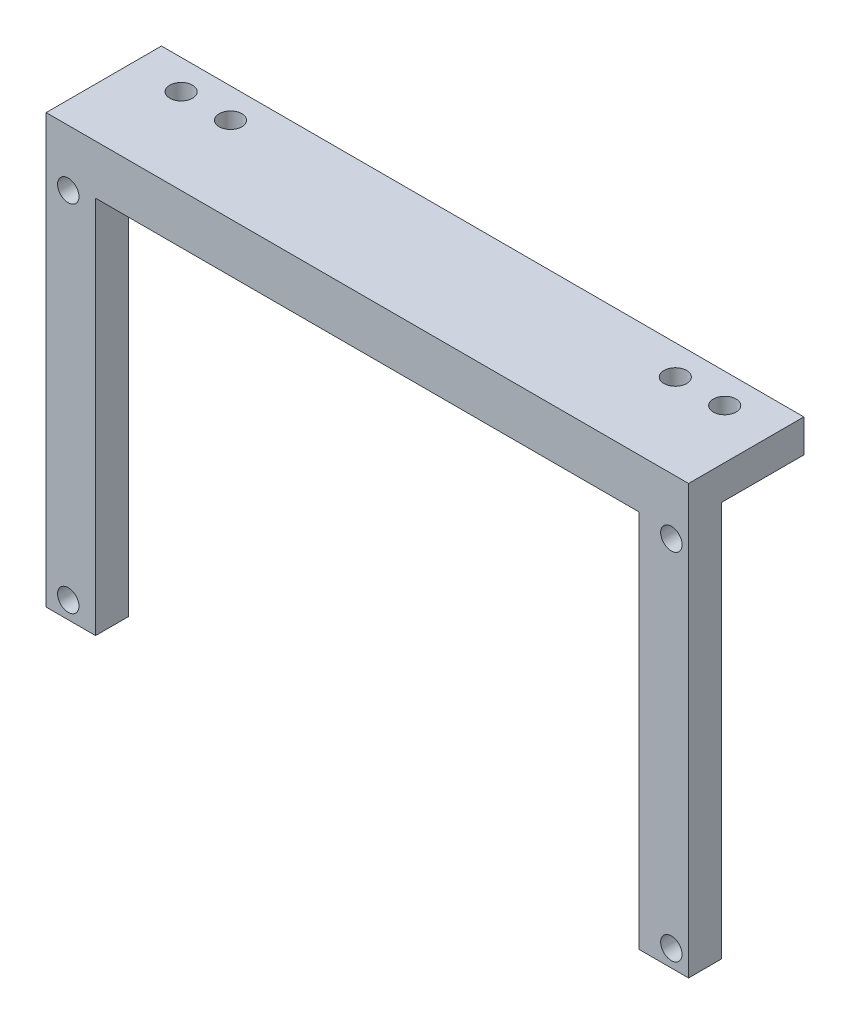
SolidWorks part; units mm, degrees
ref_plane "Front Plane" through (0, 0, 0) normal (0, 0, 1) x (1, 0, 0)
ref_plane "Top Plane" through (0, 0, 0) normal (0, 1, 0) x (1, 0, 0)
ref_plane "Right Plane" through (0, 0, 0) normal (1, 0, 0) x (0, 0, -1)
sketch "Sketch1" plane through (0, 0, 0) normal (1, 0, 0) x (0, 0, -1)
  line L0 (-29.8974, 26.1815) -> (-12.1174, 26.1815)
  line L1 (-29.8974, -39.8585) -> (-24.8174, -39.8585)
  line L2 (-29.8974, -39.8585) -> (-29.8974, 26.1815)
  line L4 (-24.8174, -39.8585) -> (-24.8174, 21.1015)
  line L7 (-24.8174, 21.1015) -> (-12.1174, 21.1015)
  line L8 (-12.1174, 26.1815) -> (-12.1174, 21.1015)
  dimension "D1" = 12.7
  dimension "D2" = 60.96
  dimension "D3" = 5.08
  dimension "D4" = 12.1174
  dimension "D5" = 21.1015
extrude "Boss-Extrude1" add sketch "Sketch1" along normal blind 99.06
sketch "Sketch2" plane through (0, 0, 0) normal (0, 0, 1) x (1, 0, 0)
  line L3 (7.62, 18.5615) -> (91.44, 18.5615)
  line L4 (91.44, -42.3985) -> (91.44, 18.5615)
  line L5 (99.06, 21.1015) -> (0, 21.1015) construction
  line L6 (7.62, 18.5615) -> (7.62, -42.3985)
  line L7 (91.44, -42.3985) -> (7.62, -42.3985)
  line L8 (99.06, -39.8585) -> (99.06, 21.1015) construction
  line L9 (0, -39.8585) -> (0, 21.1015) construction
  dimension "D1" = 2.54
  dimension "D2" = 60.96
  dimension "D3" = 7.62
  dimension "D4" = 7.62
extrude "Cut-Extrude1" cut sketch "Sketch2" along normal blind 86.106
sketch "Sketch3" plane through (0, 0, 0) normal (0, 0, 1) x (1, 0, 0)
  circle A0 centre (96.41, -37.2085) radius 1.65
  circle A1 centre (96.41, 17.4915) radius 1.65
  circle A2 centre (3.41, 17.4915) radius 1.65
  circle A3 centre (3.41, -37.2085) radius 1.65
  dimension "D1" = 3.3
extrude "Cut-Extrude2" cut sketch "Sketch3" along normal blind 228.6
sketch "Sketch4" plane through (0, 0, 0) normal (0, 1, 0) x (1, 0, 0)
  line L0 (49.53, -12.1174) -> (49.53, -35.7436) construction
  line L1 (99.06, -12.1174) -> (0, -12.1174) construction
  line L2 (0, -12.1174) -> (0, -29.8974) construction
  circle A0 centre (7.62, -16.7022) radius 1.7526
  circle A1 centre (15.24, -16.7022) radius 1.7526
  circle A2 centre (83.82, -16.7022) radius 1.7526
  circle A3 centre (91.44, -16.7022) radius 1.7526
  dimension "D3" = 3.5052
  dimension "D1" = 7.62
  dimension "D2" = 7.62
  dimension "D4" = 16.7022
extrude "Cut-Extrude3" cut sketch "Sketch4" along normal blind 228.6
